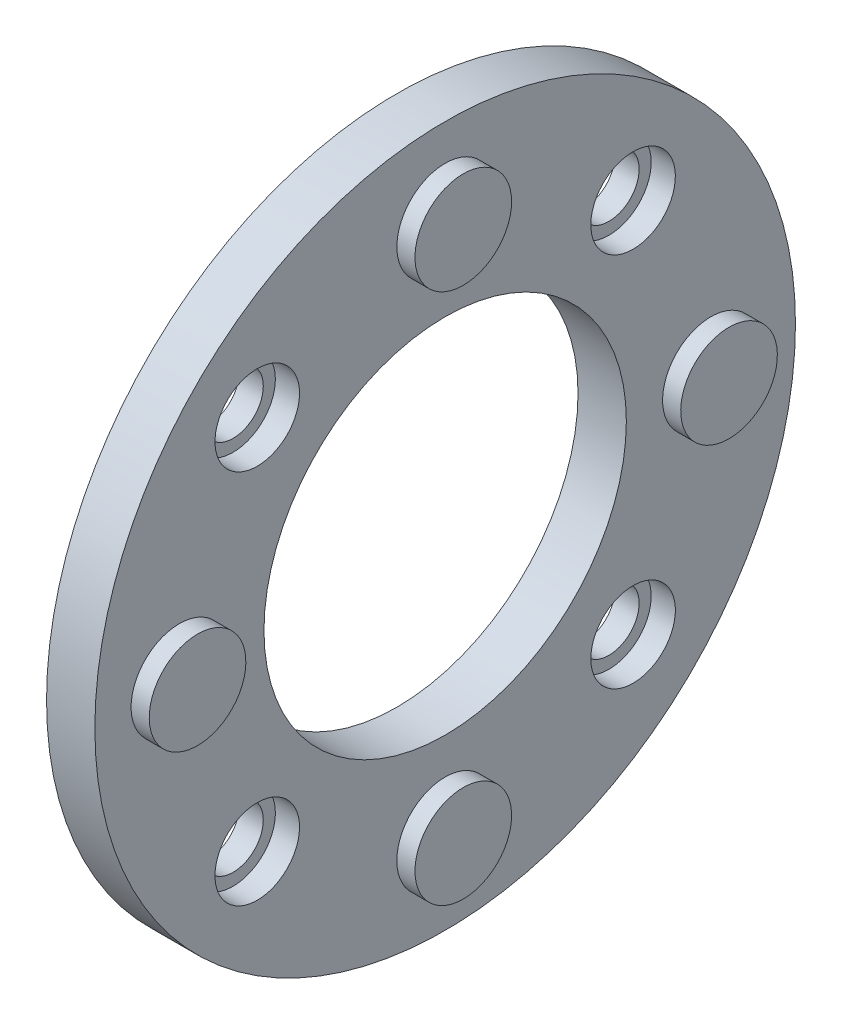
SolidWorks part; units mm, degrees
ref_plane "前视基准面" through (0, 0, 0) normal (0, 0, 1) x (1, 0, 0)
ref_plane "上视基准面" through (0, 0, 0) normal (0, 1, 0) x (1, 0, 0)
ref_plane "右视基准面" through (0, 0, 0) normal (1, 0, 0) x (0, 0, -1)
other "Configuration Table"
sketch "草图1" plane through (0, 0, 0) normal (1, 0, 0) x (0, 0, -1)
  circle A0 centre (0, 0) radius 29
  dimension "D1" = 58
extrude "凸台-拉伸1" add sketch "草图1" along normal blind 4
sketch "草图2" plane through (4, 0, 0) normal (1, 0, 0) x (0, 0, -1)
  circle A0 centre (0, 0) radius 15
  dimension "D1" = 30
extrude "切除-拉伸1" cut sketch "草图2" against normal through all both and the other way through all
sketch "草图4" plane through (4, 0, 0) normal (1, 0, 0) x (0, 0, -1)
  line L0 (0, 22) -> (0, 0)
  circle A0 centre (0, 0) radius 22 construction
  circle A1 centre (0, 22) radius 4
  dimension "D1" = 44
  dimension "D2" = 8
extrude "凸台-拉伸3" add sketch "草图4" along normal blind 1.5 and the other way blind 5
pattern_circular "阵列(圆周)1" count 4 over 360 about axis through (0, 0, 0) along (1, 0, 0) of "凸台-拉伸3"
sketch "草图5" plane through (-1, 0, 0) normal (-1, 0, 0) x (0, 0, 1)
  circle A0 centre (0, 22) radius 2.5
  dimension "5" = 5
extrude "切除-拉伸2" cut sketch "草图5" against normal blind 4.5
pattern_circular "阵列(圆周)2" count 4 over 360 about axis through (0, 0, 0) along (1, 0, 0) of "切除-拉伸2"
sketch "草图7" plane through (4, 0, 0) normal (1, 0, 0) x (0, 0, -1)
  line L0 (0, 0) -> (-15.5563, 15.5563)
  circle A0 centre (0, 0) radius 22
  circle A1 centre (-15.5563, 15.5563) radius 2.5
  dimension "D1" = 5
  dimension "44" = 44
extrude "切除-拉伸3" cut sketch "草图7" against normal through all contours A0 A1 | A0 A1 L0 | L0 A1 A0
sketch "草图8" plane through (4, 0, 0) normal (1, 0, 0) x (0, 0, -1)
  circle A0 centre (-15.5563, 15.5563) radius 3.5
  dimension "D1" = 7
extrude "切除-拉伸4" cut sketch "草图8" against normal blind 2
pattern_circular "阵列(圆周)3" count 4 over 360 about axis through (0, 0, 0) along (1, 0, 0) of "切除-拉伸4", "切除-拉伸3"
